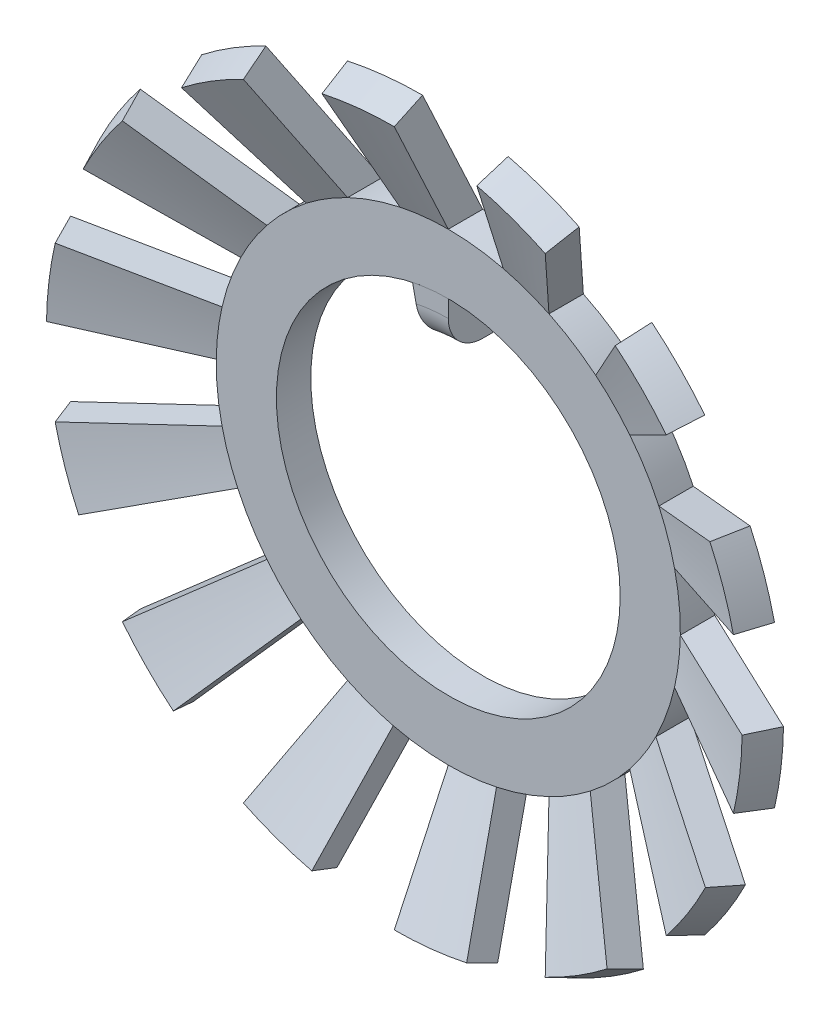
SolidWorks part; units mm, degrees
ref_plane "Front Plane" through (0, 0, 0) normal (0, 0, 1) x (1, 0, 0)
ref_plane "Top Plane" through (0, 0, 0) normal (0, 1, 0) x (1, 0, 0)
ref_plane "Right Plane" through (0, 0, 0) normal (1, 0, 0) x (0, 0, -1)
ref_axis "Axis1" through (0, 0, -0.1285) along (0, 0, 1)
sketch "Sketch1" plane through (0, 0, 0) normal (0, 0, 1) x (1, 0, 0)
  circle A0 centre (0, 0) radius 6.75
extrude "Boss-Extrude1" add sketch "Sketch1" along normal blind 1
sketch "Sketch2" plane through (0, 0, 1) normal (0, 0, 1) x (1, 0, 0)
  circle A0 centre (0, 0) radius 5
extrude "Cut-Extrude1" cut sketch "Sketch2" against normal blind 1
sketch "Sketch3" plane through (0, 0, 0) normal (1, 0, 0) x (0, 0, -1)
  line L0 (0, 6.75) -> (-1.7489, 10.5006)
  line L1 (-1, 6.75) -> (-2.5703, 10.1176)
  line L2 (-1.7489, 10.5006) -> (-2.5703, 10.1176)
  line L3 (-1, 6.75) -> (0, 6.75)
  dimension "D1" = 4.1383
  dimension "D2" = 0.9063
revolve "Revolve3" add sketch "Sketch3" angle 12 about axis through (0, 0, -0.1285) along (0, 0, 1)
pattern_circular "CirPattern1" count 14 over 360 about axis through (0, 0, 0) along (0, 0, 1) of "Revolve3"
sketch "Sketch4" plane through (0, 0, 0) normal (1, 0, 0) x (0, 0, -1)
  line L1 (0, 3.5) -> (1, 3.5)
  line L4 (1, 3.5) -> (1, 5)
  line L5 (0, 3.5) -> (1, 5) construction
  line L6 (1, 5) -> (1, 3.5) construction
  line L10 (1, 5) -> (-1, 5)
  line L11 (-1, 4.5) -> (-1, 5)
  line L12 (0, 4.5) -> (-1, 5) construction
  line L13 (1, 5) -> (-1, 4.5) construction
  arc A0 (-1, 4.5) -> (0, 3.5) centre (0, 4.5) ccw
  point P4 (0.2606, 6.1226)
  point P7 (-0.5, 4.75)
  point P8 (0, 0)
  point P10 (0, 0)
revolve "Revolve4" add sketch "Sketch4" angle 12 about axis through (0, 0, -0.1285) along (0, 0, 1)
